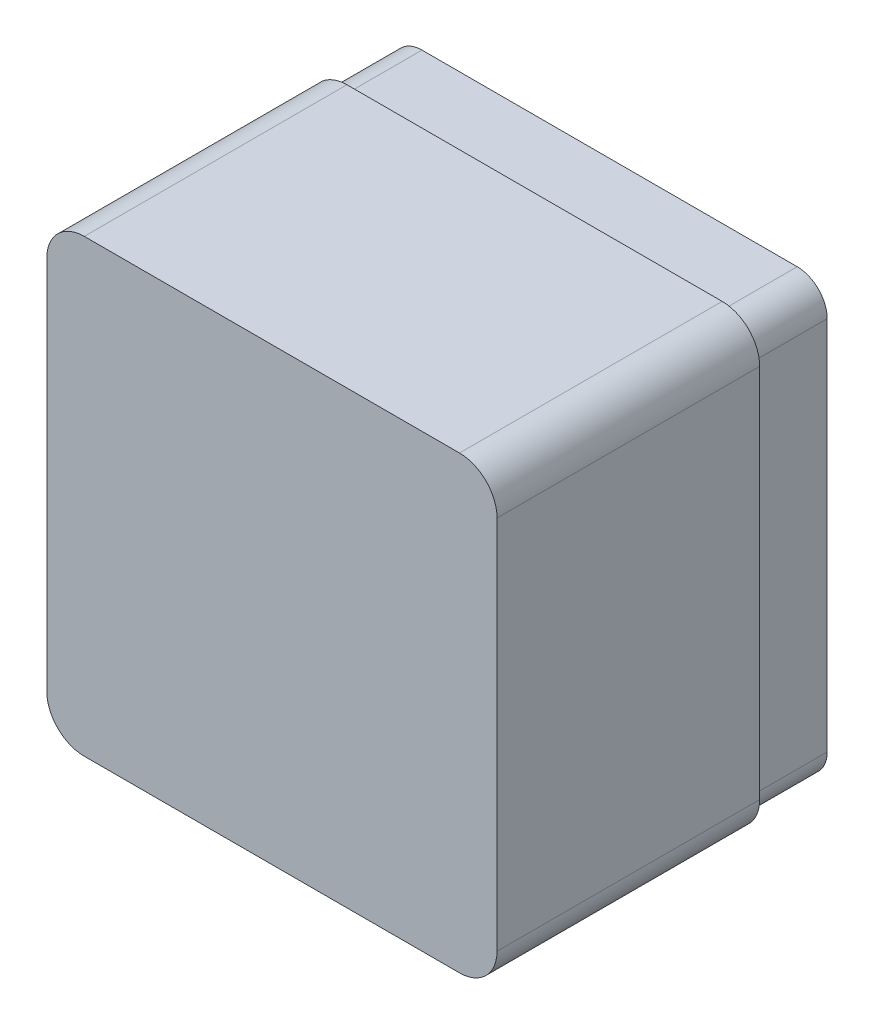
SolidWorks part; units mm, degrees
ref_plane "Front Plane" through (0, 0, 0) normal (0, 0, 1) x (1, 0, 0)
ref_plane "Top Plane" through (0, 0, 0) normal (0, 1, 0) x (1, 0, 0)
ref_plane "Right Plane" through (0, 0, 0) normal (1, 0, 0) x (0, 0, -1)
sketch "Sketch1" plane through (0, 0, 0) normal (0, 0, 1) x (1, 0, 0)
  line L1 (0, 0) -> (120, 0)
  line L2 (0, 0) -> (0, 120)
  line L3 (0, 120) -> (120, 120)
  line L4 (120, 0) -> (120, 120)
  dimension "D1" = 120
extrude "Boss-Extrude1" add sketch "Sketch1" along normal blind 90
fillet "Fillet1" radius 10 4 edges at (0, 0, 45) (120, 0, 45) (120, 120, 45) (0, 120, 45)
shell "Shell1" thickness 4
sketch "Sketch2" plane through (0, 0, 0) normal (0, 0, -1) x (-1, 0, 0)
  line L0 (-110, 2) -> (-10, 2)
  line L1 (-2, 10) -> (-2, 110)
  line L2 (-10, 118) -> (-110, 118)
  line L3 (-118, 110) -> (-118, 10)
  line L4 (-110, 0) -> (-10, 0)
  line L5 (0, 10) -> (0, 110)
  line L6 (-10, 120) -> (-110, 120)
  line L7 (-120, 110) -> (-120, 10)
  line L8 (-110, 0) -> (-10, 0)
  line L9 (0, 10) -> (0, 110)
  line L10 (-10, 120) -> (-110, 120)
  line L11 (-120, 110) -> (-120, 10)
  arc A0 (-10, 2) -> (-2, 10) centre (-10, 10) ccw
  arc A1 (-2, 110) -> (-10, 118) centre (-10, 110) ccw
  arc A2 (-110, 118) -> (-118, 110) centre (-110, 110) ccw
  arc A3 (-118, 10) -> (-110, 2) centre (-110, 10) ccw
  arc A4 (-10, 0) -> (0, 10) centre (-10, 10) ccw
  arc A5 (0, 110) -> (-10, 120) centre (-10, 110) ccw
  arc A6 (-110, 120) -> (-120, 110) centre (-110, 110) ccw
  arc A7 (-120, 10) -> (-110, 0) centre (-110, 10) ccw
  arc A8 (-10, 0) -> (0, 10) centre (-10, 10) ccw
  arc A9 (0, 110) -> (-10, 120) centre (-10, 110) ccw
  arc A10 (-110, 120) -> (-120, 110) centre (-110, 110) ccw
  arc A11 (-120, 10) -> (-110, 0) centre (-110, 10) ccw
  dimension "D1" = 0
  dimension "D2" = 2
extrude "Cut-Extrude1" cut sketch "Sketch2" against normal blind 20
